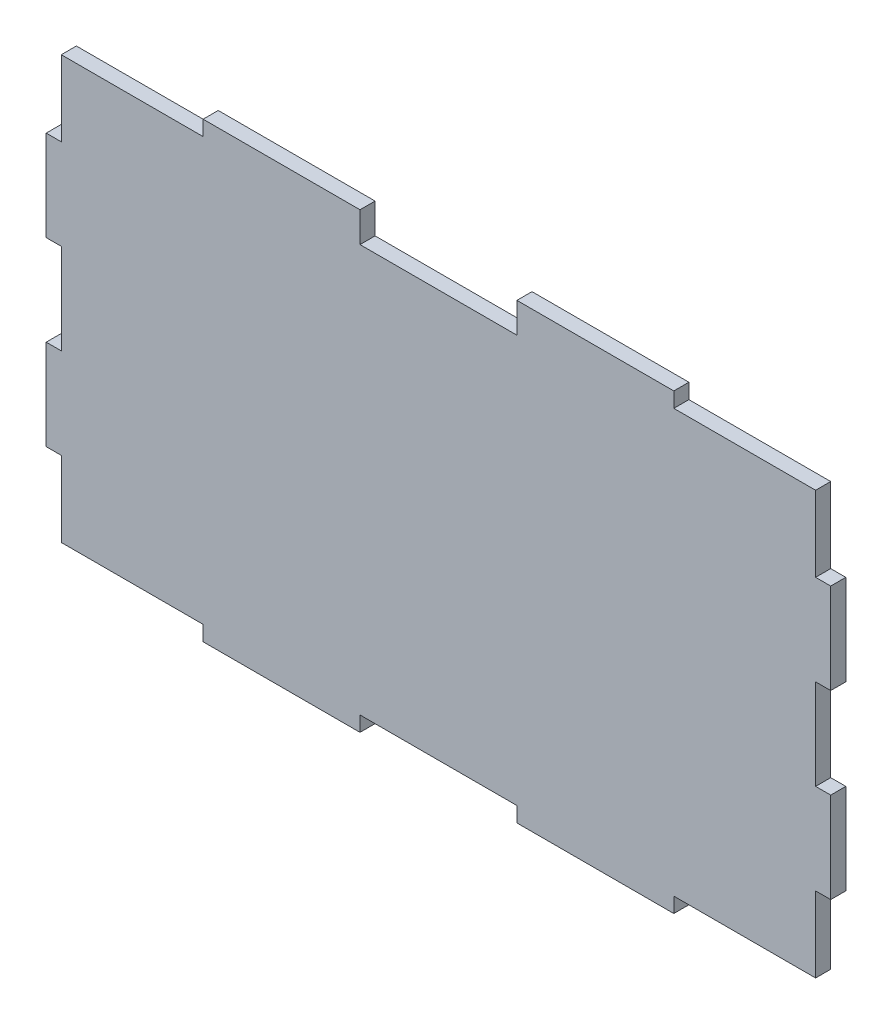
SolidWorks part; units mm, degrees
ref_plane "Alzado" through (0, 0, 0) normal (0, 0, 1) x (1, 0, 0)
ref_plane "Planta" through (0, 0, 0) normal (0, 1, 0) x (1, 0, 0)
ref_plane "Vista lateral" through (0, 0, 0) normal (1, 0, 0) x (0, 0, -1)
sketch "Croquis1" plane through (0, 0, 0) normal (0, 0, 1) x (1, 0, 0)
  line L0 (130, 150) -> (130, 129.9372) construction
  line L1 (52, 0) -> (104, 0)
  line L2 (0, 30) -> (0, 60)
  line L3 (52, 150) -> (104, 150)
  line L4 (260, 30) -> (260, 60)
  line L5 (0, 75) -> (16.5526, 75) construction
  line L6 (0, 120) -> (5, 120)
  line L7 (0, 90) -> (0, 120)
  line L8 (5, 90) -> (0, 90)
  line L9 (0, 30) -> (5, 30)
  line L10 (0, 0) -> (5, 0) construction
  line L11 (5, 60) -> (0, 60)
  line L12 (5, 30) -> (5, 5)
  line L13 (5, 60) -> (5, 90)
  line L14 (5, 120) -> (5, 145)
  line L15 (0, 30) -> (0, 0) construction
  line L16 (255, 30) -> (255, 5)
  line L17 (260, 30) -> (255, 30)
  line L18 (255, 60) -> (260, 60)
  line L19 (255, 60) -> (255, 90)
  line L20 (255, 90) -> (260, 90)
  line L21 (260, 120) -> (255, 120)
  line L22 (255, 120) -> (255, 145)
  line L23 (260, 90) -> (260, 120)
  line L24 (52, 150) -> (52, 145)
  line L25 (208, 5) -> (255, 5)
  line L26 (104, 145) -> (104, 150)
  line L27 (208, 150) -> (208, 145)
  line L28 (156, 145) -> (156, 150)
  line L29 (208, 0) -> (208, 5)
  line L30 (52, 145) -> (5, 145)
  line L31 (104, 145) -> (156, 145)
  line L32 (208, 145) -> (255, 145)
  line L33 (156, 150) -> (208, 150)
  line L34 (156, 5) -> (156, 0)
  line L35 (104, 5) -> (156, 5)
  line L36 (104, 5) -> (104, 0)
  line L37 (52, 0) -> (52, 5)
  line L38 (52, 5) -> (5, 5)
  line L39 (156, 0) -> (208, 0)
  line L40 (0, 0) -> (52, 0) construction
  dimension "D1" = 5
  dimension "D2" = 260
  dimension "D3" = 5
  dimension "D4" = 30
  dimension "D5" = 30
  dimension "D6" = 52
  dimension "D7" = 52
  dimension "D8" = 5
  dimension "D9" = 150
  dimension "D10" = 52
  dimension "D11" = 25
extrude "Saliente-Extruir1" add sketch "Croquis1" along normal blind 5
sketch "Croquis2" plane through (0, 0, 5) normal (0, 0, 1) x (1, 0, 0)
  line L0 (156, 150) -> (156, 145) construction
  line L1 (104, 145) -> (156, 145)
  line L2 (104, 145) -> (104, 140)
  line L3 (104, 140) -> (156, 140)
  line L4 (156, 145) -> (156, 140)
  dimension "D1" = 5
extrude "Cortar-Extruir1" cut sketch "Croquis2" against normal blind 10
